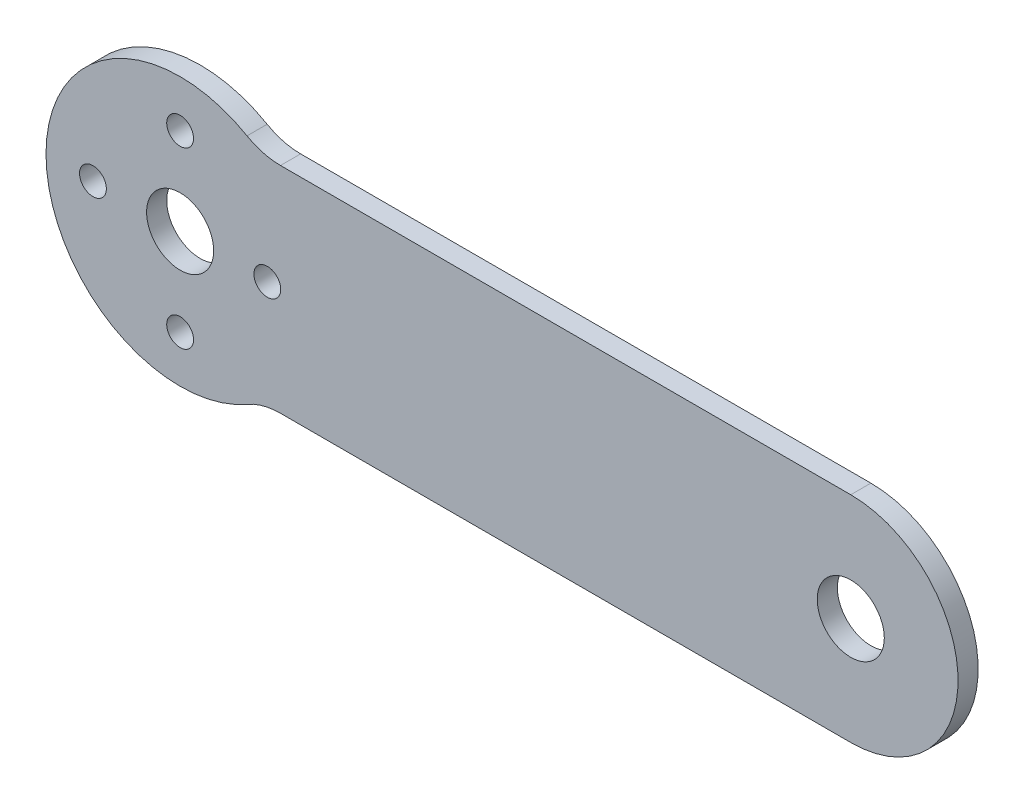
SolidWorks part; units mm, degrees
ref_plane "Front" through (0, 0, 0) normal (0, 0, 1) x (1, 0, 0)
ref_plane "Top" through (0, 0, 0) normal (0, 1, 0) x (1, 0, 0)
ref_plane "Right" through (0, 0, 0) normal (1, 0, 0) x (0, 0, -1)
sketch "草图1" plane through (0, 0, 0) normal (0, 0, 1) x (1, 0, 0)
  line L0 (0, 0) -> (100, 0) construction
  line L2 (0, 16) -> (100, 16)
  line L3 (0, -16) -> (100, -16)
  arc A0 (0, 16) -> (0, -16) centre (0, 0) ccw
  arc A1 (100, -16) -> (100, 16) centre (100, 0) ccw
  point P6 (50, 0)
  dimension "D1" = 16
  dimension "D2" = 100
extrude "凸台-拉伸1" add sketch "草图1" along normal blind 3
sketch "草图2" plane through (0, 0, 3) normal (0, 0, 1) x (1, 0, 0)
  line L0 (100, 16) -> (0, 16) construction
  circle A0 centre (0, 0) radius 20
  dimension "D1" = 40
  dimension "D2" = 16
extrude "凸台-拉伸2" add sketch "草图2" against normal blind 3
fillet "圆角1" radius 10 2 edges at (12, -16, 1.5) (12, 16, 1.5)
sketch "草图3" plane through (0, 0, 3) normal (0, 0, 1) x (1, 0, 0)
  circle A0 centre (0, 13) radius 2
  circle A1 centre (13, 0) radius 2
  circle A2 centre (0, -13) radius 2
  circle A3 centre (-13, 0) radius 2
  circle A4 centre (0, 0) radius 5
  circle A5 centre (100, 0) radius 5
  point P12 (0, 0)
  dimension "D1" = 4
  dimension "D4" = 10
  dimension "D5" = 10
  dimension "D2" = 13
  dimension "D3" = 4
extrude "切除-拉伸1" cut sketch "草图3" against normal blind 3
